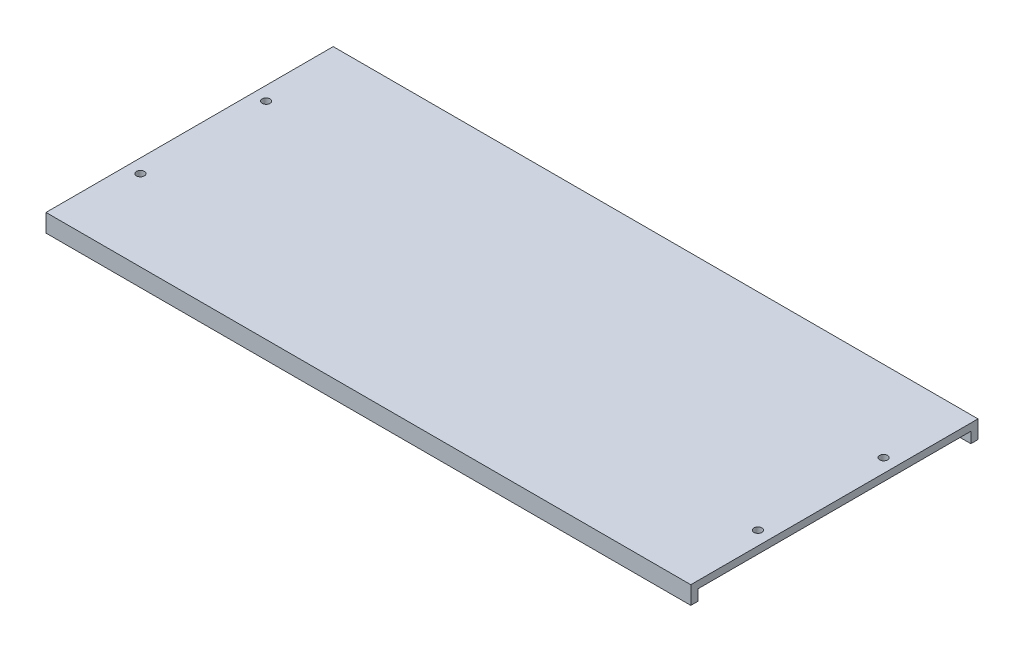
SolidWorks part; units mm, degrees
ref_plane "前视基准面" through (0, 0, 0) normal (0, 0, 1) x (1, 0, 0)
ref_plane "上视基准面" through (0, 0, 0) normal (0, 1, 0) x (1, 0, 0)
ref_plane "右视基准面" through (0, 0, 0) normal (1, 0, 0) x (0, 0, -1)
other "Configuration Table"
sketch "草图1" plane through (0, 0, 0) normal (0, 1, 0) x (1, 0, 0)
  line L0 (-94.7802, 0) -> (105.2085, 0) construction
  line L1 (-89.8, -38) -> (89.8, -38)
  line L2 (-89.8, -38) -> (-89.8, 38)
  line L3 (-89.8, 38) -> (89.8, 38)
  line L4 (89.8, -38) -> (89.8, 38)
  line L5 (-89.8, -38) -> (89.8, 38) construction
  line L6 (-89.8, 38) -> (89.8, -38) construction
  line L7 (0, 72.1386) -> (0, -72.7943) construction
  circle A0 centre (-86, 17.5) radius 1.1
  circle A1 centre (-86, -17.5) radius 1.1
  circle A2 centre (86, -17.5) radius 1.1
  circle A3 centre (86, 17.5) radius 1.1
  point P0 (0, 0)
  dimension "D3" = 2.2
  dimension "D4" = 35
  dimension "D5" = 172
  dimension "D1" = 76
  dimension "D2" = 179.6
extrude "凸台-拉伸1" add sketch "草图1" along normal blind 2
sketch "草图2" plane through (0, 2, 0) normal (0, 1, 0) x (1, 0, 0)
  line L0 (-89.8, 38) -> (89.8, 38)
  line L1 (89.8, 38) -> (89.8, 40)
  line L2 (89.8, 40) -> (-89.8, 40)
  line L3 (-89.8, 40) -> (-89.8, 38)
  line L4 (-103.8001, 0) -> (97.634, 0) construction
  line L5 (-89.8, -40) -> (-89.8, -38)
  line L6 (89.8, -40) -> (-89.8, -40)
  line L7 (89.8, -38) -> (89.8, -40)
  line L8 (-89.8, -38) -> (89.8, -38)
  dimension "D1" = 2
extrude "凸台-拉伸2" add sketch "草图2" against normal blind 5
